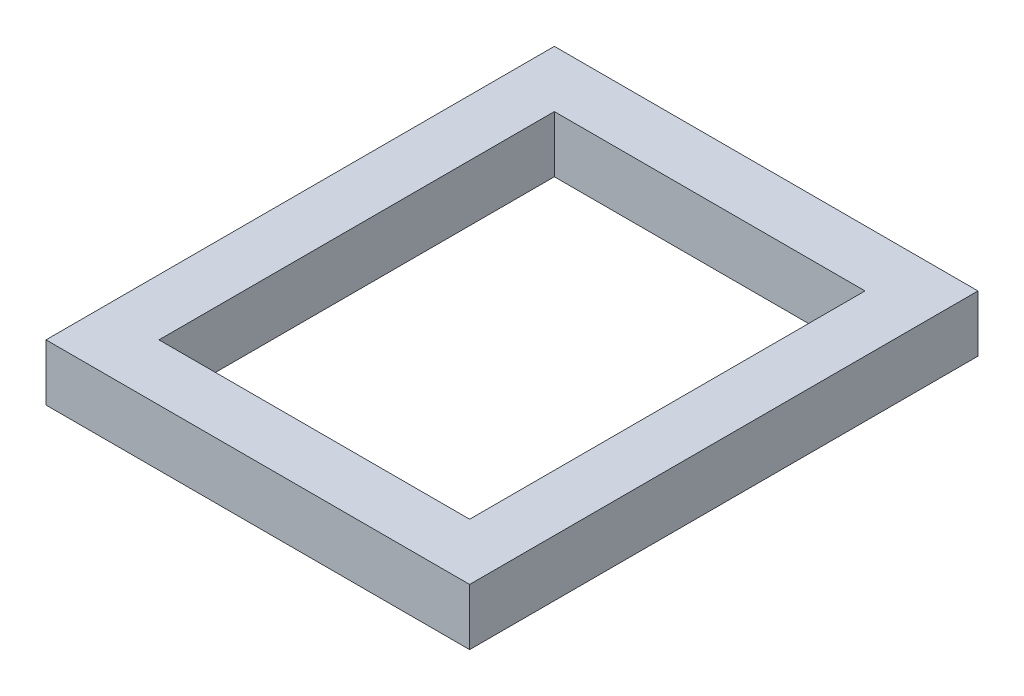
SolidWorks part; units mm, degrees
ref_plane "Front Plane" through (0, 0, 0) normal (0, 0, 1) x (1, 0, 0)
ref_plane "Top Plane" through (0, 0, 0) normal (0, 1, 0) x (1, 0, 0)
ref_plane "Right Plane" through (0, 0, 0) normal (1, 0, 0) x (0, 0, -1)
sketch "Sketch1" plane through (0, 0, 0) normal (0, 1, 0) x (1, 0, 0)
  line L1 (-47.625, -57.15) -> (47.625, -57.15)
  line L2 (-47.625, -57.15) -> (-47.625, 57.15)
  line L3 (-47.625, 57.15) -> (47.625, 57.15)
  line L4 (47.625, -57.15) -> (47.625, 57.15)
  line L5 (-47.625, -57.15) -> (47.625, 57.15) construction
  line L6 (-47.625, 57.15) -> (47.625, -57.15) construction
  line L7 (-34.925, -44.45) -> (34.925, -44.45)
  line L8 (-34.925, -44.45) -> (-34.925, 44.45)
  line L9 (-34.925, 44.45) -> (34.925, 44.45)
  line L10 (34.925, -44.45) -> (34.925, 44.45)
  line L11 (-34.925, -44.45) -> (34.925, 44.45) construction
  line L12 (-34.925, 44.45) -> (34.925, -44.45) construction
  point P0 (0, 0)
  point P5 (0, 0)
  dimension "D3" = 12.7
  dimension "D1" = 95.25
  dimension "D2" = 114.3
  dimension "D4" = 12.7
extrude "Boss-Extrude1" add sketch "Sketch1" along normal blind 12.7
